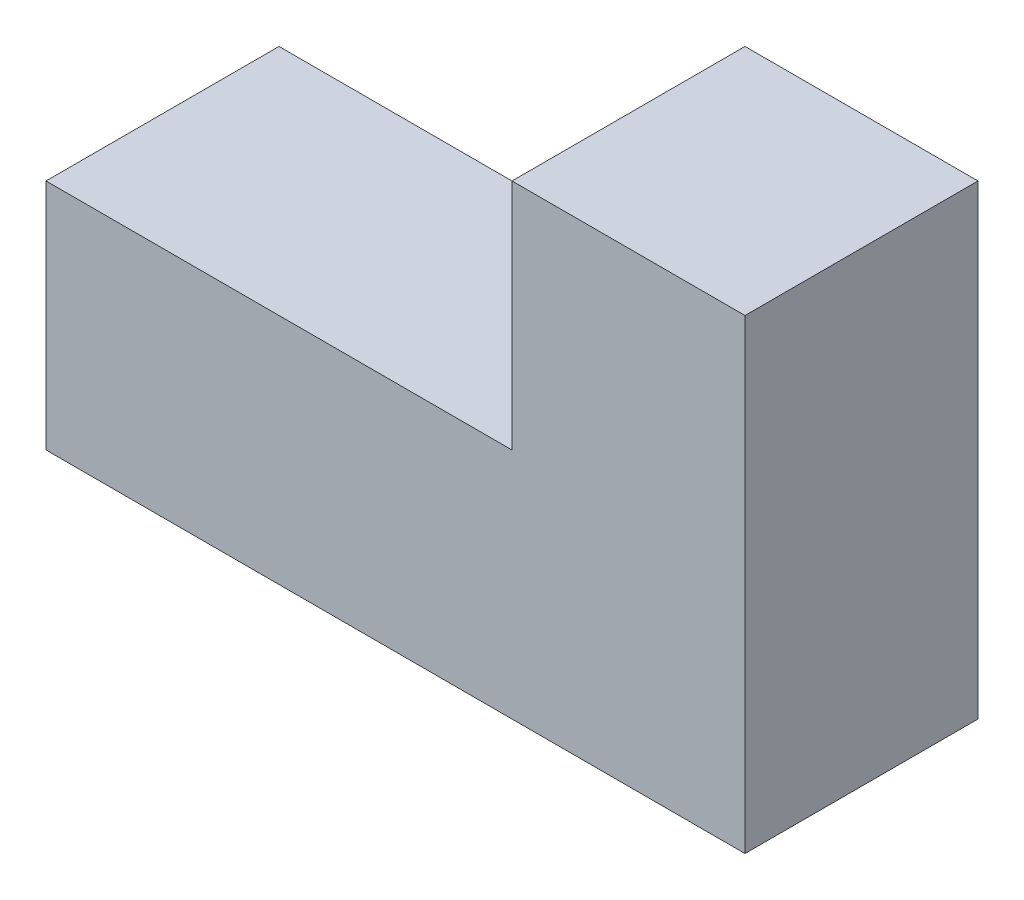
SolidWorks part; units mm, degrees
ref_plane "Plan de face" through (0, 0, 0) normal (0, 0, 1) x (1, 0, 0)
ref_plane "Plan de dessus" through (0, 0, 0) normal (0, 1, 0) x (1, 0, 0)
ref_plane "Plan de droite" through (0, 0, 0) normal (1, 0, 0) x (0, 0, -1)
sketch "Esquisse1" plane through (0, 0, 0) normal (0, 0, 1) x (1, 0, 0)
  line L0 (0, 0) -> (900, 0)
  line L1 (900, 0) -> (900, 600)
  line L2 (900, 600) -> (600, 600)
  line L3 (600, 600) -> (600, 300)
  line L4 (600, 300) -> (0, 300)
  line L5 (0, 300) -> (0, 0)
  dimension "D1" = 600
  dimension "D2" = 300
  dimension "D3" = 900
  dimension "D4" = 600
extrude "Boss.-Extru.1" add sketch "Esquisse1" along normal blind 300
